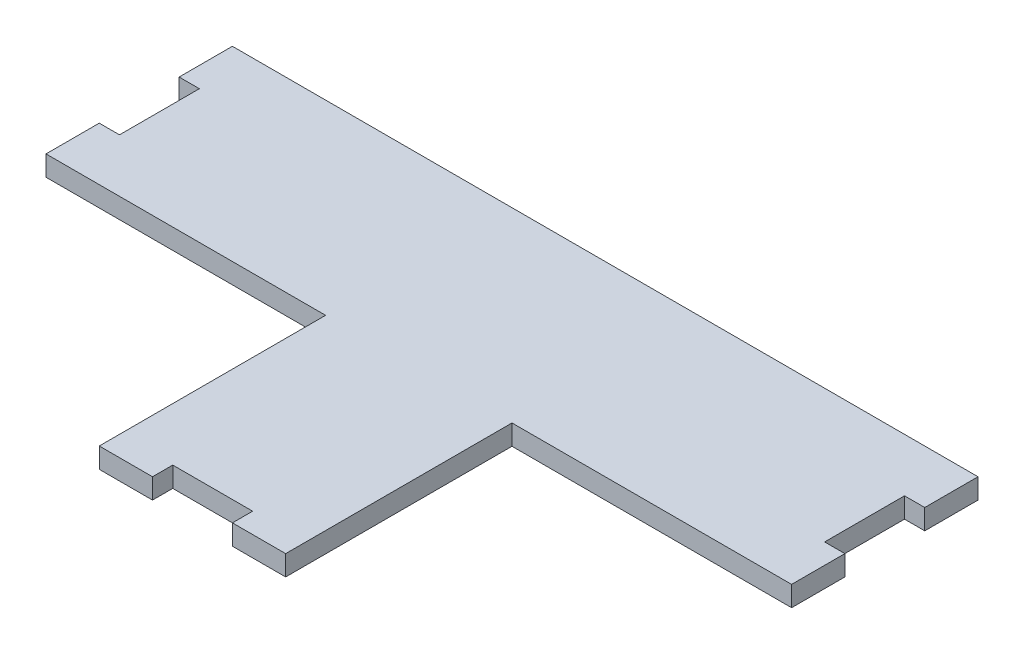
SolidWorks part; units mm, degrees
ref_plane "Front Plane" through (0, 0, 0) normal (0, 0, 1) x (1, 0, 0)
ref_plane "Top Plane" through (0, 0, 0) normal (0, 1, 0) x (1, 0, 0)
ref_plane "Right Plane" through (0, 0, 0) normal (1, 0, 0) x (0, 0, -1)
sketch "Sketch1" plane through (0, 0, 0) normal (0, 1, 0) x (1, 0, 0)
  line L1 (0, 0) -> (177.8, 0)
  line L2 (0, 0) -> (0, 98.425)
  line L3 (0, 98.425) -> (177.8, 98.425)
  line L4 (177.8, 0) -> (177.8, 98.425)
  dimension "D1" = 177.8
  dimension "D2" = 98.425
extrude "Boss-Extrude1" add sketch "Sketch1" along normal blind 4.826
sketch "Sketch2" plane through (0, 4.826, 0) normal (0, 1, 0) x (1, 0, 0)
  line L0 (0, 98.425) -> (0, 0) construction
  line L1 (0, 85.725) -> (4.826, 85.725)
  line L2 (0, 85.725) -> (0, 66.675)
  line L3 (0, 66.675) -> (4.826, 66.675)
  line L4 (4.826, 85.725) -> (4.826, 66.675)
  line L5 (177.8, 0) -> (177.8, 98.425) construction
  line L6 (177.8, 85.725) -> (172.974, 85.725)
  line L7 (177.8, 85.725) -> (177.8, 66.675)
  line L8 (177.8, 66.675) -> (172.974, 66.675)
  line L9 (172.974, 85.725) -> (172.974, 66.675)
  line L10 (0, 0) -> (177.8, 0) construction
  line L11 (79.375, 0) -> (98.425, 0)
  line L12 (79.375, 0) -> (79.375, 4.826)
  line L13 (79.375, 4.826) -> (98.425, 4.826)
  line L14 (98.425, 0) -> (98.425, 4.826)
  line L15 (79.375, 4.826) -> (0, 4.826) construction
  line L16 (98.425, 4.826) -> (177.8, 4.826) construction
  line L17 (172.974, 85.725) -> (172.974, 98.425) construction
  line L18 (177.8, 98.425) -> (0, 98.425) construction
  line L19 (172.974, 66.675) -> (172.974, 0) construction
  line L20 (4.826, 66.675) -> (4.826, 0) construction
  line L21 (4.826, 85.725) -> (4.826, 98.425) construction
  dimension "D1" = 19.05
  dimension "D2" = 12.7
  dimension "D3" = 4.826
extrude "All Slots" cut sketch "Sketch2" against normal through all
sketch "Sketch3" plane through (0, 4.826, 0) normal (0, 1, 0) x (1, 0, 0)
  line L0 (66.675, 53.975) -> (66.675, 98.425) construction
  line L1 (0, 0) -> (66.675, 0)
  line L2 (0, 0) -> (0, 53.975)
  line L3 (0, 53.975) -> (66.675, 53.975)
  line L4 (66.675, 0) -> (66.675, 53.975)
  line L5 (177.8, 98.425) -> (0, 98.425) construction
  line L7 (177.8, 0) -> (111.125, 0)
  line L8 (177.8, 0) -> (177.8, 53.975)
  line L9 (177.8, 53.975) -> (111.125, 53.975)
  line L10 (111.125, 0) -> (111.125, 53.975)
  dimension "D1" = 66.675
  dimension "D2" = 53.975
extrude "Cut-Extrude2" cut sketch "Sketch3" against normal through all
equation "\"material\"= \"gmaterial@Forklift_Assembly.assembly\""
equation "\"D1@Boss-Extrude1\"=\"material\""
equation "\"D3@Sketch2\"=\"material\""
